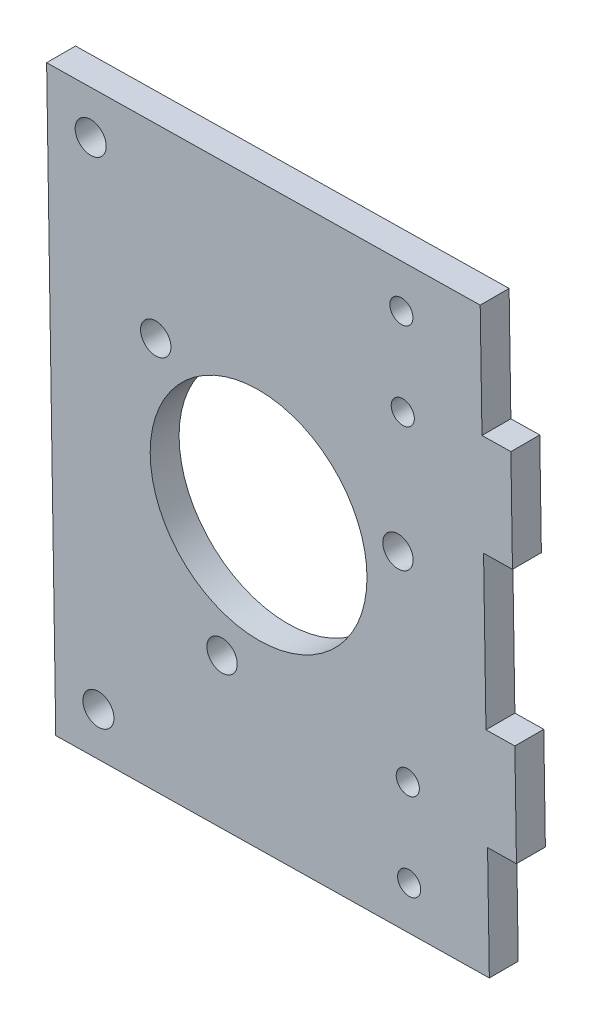
SolidWorks part; units mm, degrees
ref_plane "前视基准面" through (0, 0, 0) normal (0, 0, 1) x (1, 0, 0)
ref_plane "上视基准面" through (0, 0, 0) normal (0, 1, 0) x (1, 0, 0)
ref_plane "右视基准面" through (0, 0, 0) normal (1, 0, 0) x (0, 0, -1)
sketch "草图2" plane through (0, 0, 0) normal (0, 0, 1) x (1, 0, 0)
  line L0 (131.1378, 89.3743) -> (132.4009, 9.3743)
  line L1 (132.4009, 9.3743) -> (72.4083, 8.4271)
  line L2 (72.4083, 8.4271) -> (71.1453, 88.4271)
  line L3 (71.1453, 88.4271) -> (131.1378, 89.3743)
  dimension "D1" = 60
  dimension "D2" = 80
extrude "凸台-拉伸1" add sketch "草图2" along normal blind 4
sketch "草图3" plane through (0, 0, 4) normal (0, 0, 1) x (1, 0, 0)
  circle A0 centre (100.4733, 48.8851) radius 15
  circle A1 centre (119.7593, 54.1817) radius 2.1
  circle A2 centre (95.4173, 29.5348) radius 2.1
  circle A3 centre (86.2434, 62.939) radius 2.1
  point P8 (100.4733, 48.8851)
  point P10 (85.2168, 61.8172)
  point P12 (96.9021, 29.2066)
  point P14 (119.3011, 55.6316)
  point P16 (21.3222, 47.6355)
  point P17 (100.4733, 48.8851)
  point P18 (7.0923, 61.6893)
  point P19 (90.9877, 65.7394)
  point P20 (85.9062, 62.6029)
  point P21 (119.2553, 52.7369)
  point P22 (119.7593, 54.1817)
  point P23 (95.4173, 29.5348)
  dimension "D1" = 30
  dimension "D2" = 4.2
extrude "切除-拉伸1" cut sketch "草图3" against normal blind 4
sketch "草图4" plane through (0, 0, 4) normal (0, 0, 1) x (1, 0, 0)
  circle A0 centre (77.2393, 82.5225) radius 2.15
  circle A1 centre (78.3127, 14.531) radius 2.15
  point P4 (78.7706, 80.5465)
  point P6 (79.781, 16.5545)
extrude "切除-拉伸2" cut sketch "草图4" against normal blind 4
sketch "草图5" plane through (0, 0, 4) normal (0, 0, 1) x (1, 0, 0)
  circle A0 centre (120.2339, 83.2014) radius 1.6
  circle A1 centre (120.4233, 71.2028) radius 1.6
  circle A2 centre (121.1179, 27.2083) radius 1.6
  circle A3 centre (121.3074, 15.2098) radius 1.6
  point P8 (120.2339, 83.2014)
  point P10 (120.4233, 71.2028)
  point P12 (121.1179, 27.2083)
  point P14 (121.3074, 15.2098)
extrude "切除-拉伸3" cut sketch "草图5" against normal blind 4
sketch "草图6" plane through (0, 0, 4) normal (0, 0, 1) x (1, 0, 0)
  line L0 (132.156, 24.8823) -> (131.935, 38.8823)
  line L1 (132.156, 24.8823) -> (136.1555, 24.9454)
  line L2 (131.935, 38.8823) -> (135.9345, 38.9454)
  line L3 (136.1555, 24.9454) -> (135.9345, 38.9454)
  line L4 (131.1378, 89.3743) -> (132.4007, 9.3842) construction
  line L5 (135.1373, 89.4374) -> (131.1378, 89.3743) construction
  line L6 (131.6035, 59.8779) -> (131.3825, 73.8762)
  line L7 (131.6035, 59.8779) -> (135.603, 59.9411)
  line L8 (131.3825, 73.8762) -> (135.382, 73.9393)
  line L9 (135.603, 59.9411) -> (135.382, 73.9393)
  line L10 (136.4002, 9.4474) -> (132.4007, 9.3842) construction
  line L11 (135.1373, 89.4374) -> (136.4002, 9.4474) construction
  dimension "D1" = 15.5
  dimension "D2" = 14
  dimension "D3" = 15.5
  dimension "D4" = 14
extrude "凸台-拉伸2" add sketch "草图6" against normal blind 4
